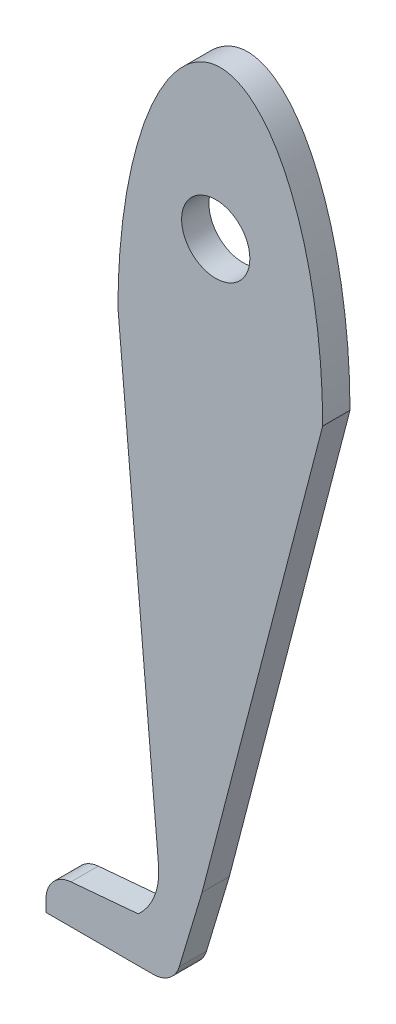
SolidWorks part; units mm, degrees
material "Pine"
ref_plane "Front Plane" through (0, 0, 0) normal (0, 0, 1) x (1, 0, 0)
ref_plane "Top Plane" through (0, 0, 0) normal (0, 1, 0) x (1, 0, 0)
ref_plane "Right Plane" through (0, 0, 0) normal (1, 0, 0) x (0, 0, -1)
sketch "Sketch1" plane through (0, 0, 0) normal (0, 0, 1) x (1, 0, 0)
  line L0 (0, 0) -> (8.8365, 34)
  line L3 (-6.1635, 34) -> (-3.1803, 0)
  line L4 (-3.1803, 0) -> (-4.6719, -3.7084)
  line L5 (-4.6719, -3.7084) -> (-11.4353, -4.3018)
  line L6 (-11.4353, -4.3018) -> (-11.4353, -7)
  line L7 (-11.4353, -7) -> (-2.1063, -7)
  line L8 (-2.1063, -7) -> (0, 0)
  ellipse E0 centre (1.3365, 34) end of major axis (1.3365, 53) minor radius 7.5 (8.8365, 34) -> (-6.1635, 34) ccw
  dimension "D1" = 34
  dimension "D2" = 15
  dimension "D3" = 19
  dimension "D4" = 34
  dimension "D5" = 7
extrude "Boss-Extrude1" add sketch "Sketch1" along normal blind 2
fillet "Fillet2" radius 2 1 edges at (-11.4353, -4.3018, 1)
fillet "Fillet3" radius 2 1 edges at (-2.1063, -7, 1)
sketch "Sketch4" plane through (0, 0, 2) normal (0, 0, 1) x (1, 0, 0)
  line L0 (-3.1803, 0) -> (-4.6719, -3.7084) construction
  line L1 (-3.1803, 0) -> (-4.6719, -3.7084)
  arc A0 (-3.1803, 0) -> (-4.6719, -3.7084) centre (-7.7792, -0.3044) cw
extrude "Cut-Extrude4" cut sketch "Sketch4" against normal blind 2
sketch "Sketch2" plane through (0, 0, 2) normal (0, 0, 1) x (1, 0, 0)
  circle A1 centre (1, 41.95) radius 2.5
  dimension "D1" = 5
extrude "Cut-Extrude5" cut sketch "Sketch2" against normal blind 2
